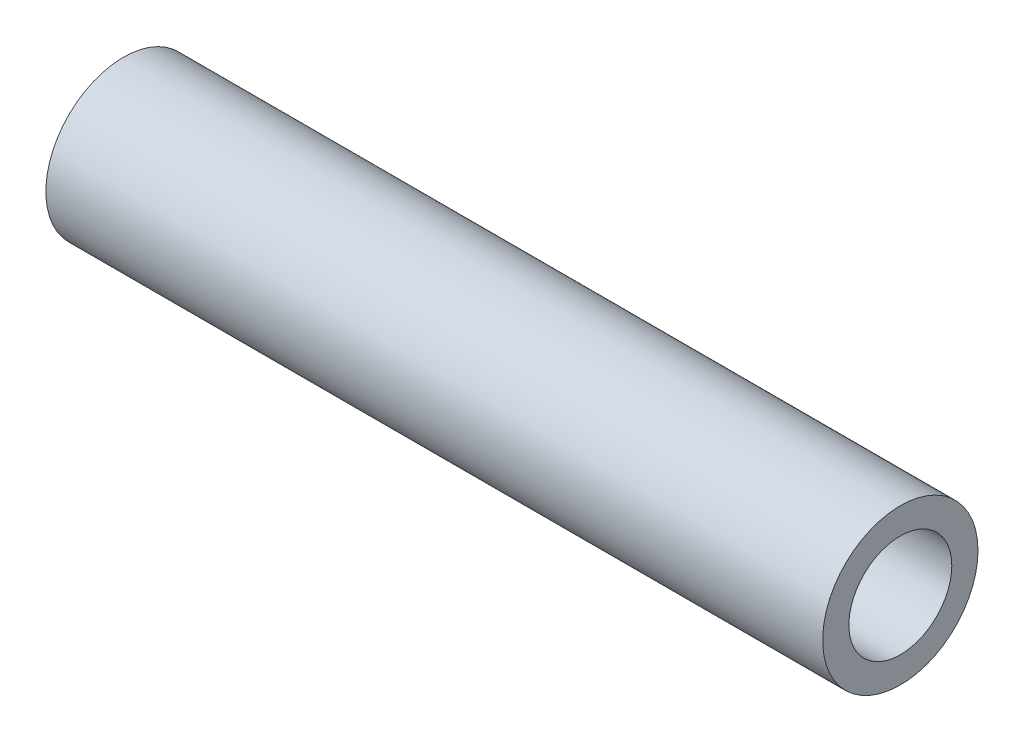
SolidWorks part; units mm, degrees
ref_plane "Front Plane" through (0, 0, 0) normal (0, 0, 1) x (1, 0, 0)
ref_plane "Top Plane" through (0, 0, 0) normal (0, 1, 0) x (1, 0, 0)
ref_plane "Right Plane" through (0, 0, 0) normal (1, 0, 0) x (0, 0, -1)
sketch "Sketch1" plane through (0, 0, 0) normal (1, 0, 0) x (0, 0, -1)
  circle A0 centre (0, 0) radius 2.65
  circle A1 centre (0, 0) radius 4
  dimension "D1" = 5.3
  dimension "D2" = 8
extrude "Boss-Extrude1" add sketch "Sketch1" along normal blind 40
